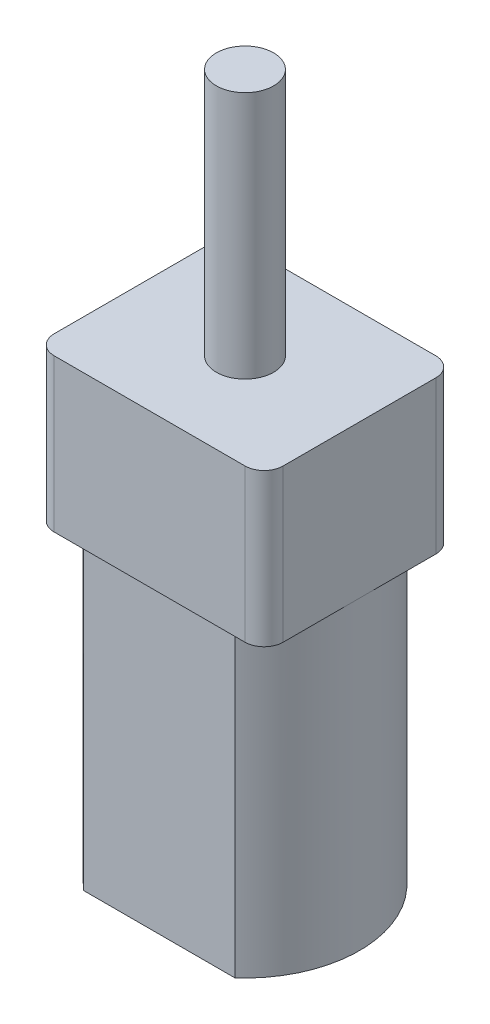
SolidWorks part; units mm, degrees
ref_plane "前视基准面" through (0, 0, 0) normal (0, 0, 1) x (1, 0, 0)
ref_plane "上视基准面" through (0, 0, 0) normal (0, 1, 0) x (1, 0, 0)
ref_plane "右视基准面" through (0, 0, 0) normal (1, 0, 0) x (0, 0, -1)
other "Configuration Table"
sketch "草图1" plane through (0, 0, 0) normal (0, 1, 0) x (1, 0, 0)
  line L1 (-6, 5) -> (6, 5)
  line L2 (-6, 5) -> (-6, -5)
  line L3 (-6, -5) -> (6, -5)
  line L4 (6, 5) -> (6, -5)
  line L5 (-6, 5) -> (6, -5) construction
  line L6 (-6, -5) -> (6, 5) construction
  point P0 (0, 0)
  dimension "D1" = 12
  dimension "D2" = 10
extrude "凸台-拉伸1" add sketch "草图1" along normal blind 24
fillet "圆角1" radius 1 4 edges at (-6, 12, -5) (6, 12, -5) (6, 12, 5) (-6, 12, 5)
sketch "草图2" plane through (0, 0, 0) normal (0, -1, 0) x (1, 0, 0)
  line L0 (-6, -4) -> (-6, 4) construction
  line L5 (-5, 5) -> (5, 5) construction
  line L6 (6, -4.5) -> (-6, -4.5)
  line L7 (6, -4.5) -> (6, 4.5)
  line L8 (6, 4.5) -> (-6, 4.5)
  line L9 (-6, -4.5) -> (-6, 4.5)
  line L10 (6, -4.5) -> (-6, 4.5) construction
  line L11 (6, 4.5) -> (-6, -4.5) construction
  circle A2 centre (0, 0) radius 6
  dimension "D1" = 0.5
extrude "切除-拉伸1" cut sketch "草图2" against normal blind 16 flip side to cut contours L6 A2 L8
sketch "草图3" plane through (0, 24, 0) normal (0, 1, 0) x (1, 0, 0)
  circle A0 centre (0, 0) radius 1.5
  dimension "D1" = 3
extrude "凸台-拉伸2" add sketch "草图3" along normal blind 13
